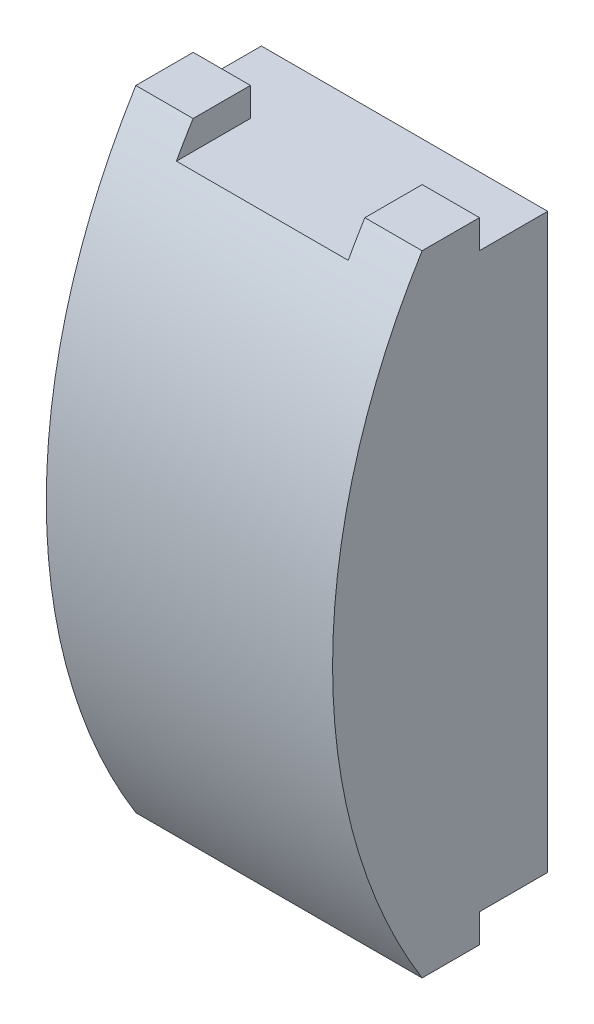
SolidWorks part; units mm, degrees
ref_plane "Front Plane" through (0, 0, 0) normal (0, 0, 1) x (1, 0, 0)
ref_plane "Top Plane" through (0, 0, 0) normal (0, 1, 0) x (1, 0, 0)
ref_plane "Right Plane" through (0, 0, 0) normal (1, 0, 0) x (0, 0, -1)
sketch "Sketch1" plane through (0, 0, 0) normal (0, 0, 1) x (1, 0, 0)
  line L1 (25, -50) -> (-25, -50)
  line L2 (25, -50) -> (25, 50)
  line L3 (25, 50) -> (-25, 50)
  line L4 (-25, -50) -> (-25, 50)
  line L5 (25, -50) -> (-25, 50) construction
  line L6 (25, 50) -> (-25, -50) construction
  point P0 (0, 0)
  dimension "D1" = 50
  dimension "D2" = 100
extrude "Boss-Extrude1" add sketch "Sketch1" along normal blind 20
sketch "Sketch2" plane through (25, 0, 0) normal (1, 0, 0) x (0, 0, -1)
  line L0 (-11.9183, 55) -> (-11.9183, -55)
  line L1 (-21.9367, -55) -> (-11.9183, -55)
  line L2 (-20, -50) -> (0, -50) construction
  line L3 (-21.9367, 55) -> (-11.9183, 55)
  line L4 (-20, 50) -> (0, 50) construction
  arc A0 (-21.9367, 55) -> (-21.9367, -55) centre (66.9973, 0) ccw
  dimension "D1" = 5
  dimension "D2" = 5
extrude "Boss-Extrude2" add sketch "Sketch2" against normal through all
sketch "Sketch3" plane through (0, 0, 0) normal (0, 0, -1) x (-1, 0, 0)
  line L0 (25, 55) -> (-25, 55) construction
  line L1 (15, 55) -> (-15, 55)
  line L2 (15, 55) -> (15, 50)
  line L3 (15, 50) -> (-15, 50)
  line L4 (-15, 55) -> (-15, 50)
  line L5 (15, 55) -> (-15, 50) construction
  line L6 (15, 50) -> (-15, 55) construction
  line L7 (0, 58.6226) -> (0, -58.9252) construction
  line L8 (25, -55) -> (25, 55) construction
  point P4 (0, 52.5)
  dimension "D1" = 10
  dimension "D2" = 5
  dimension "D3" = 30
extrude "Cut-Extrude1" cut sketch "Sketch3" against normal blind 30
